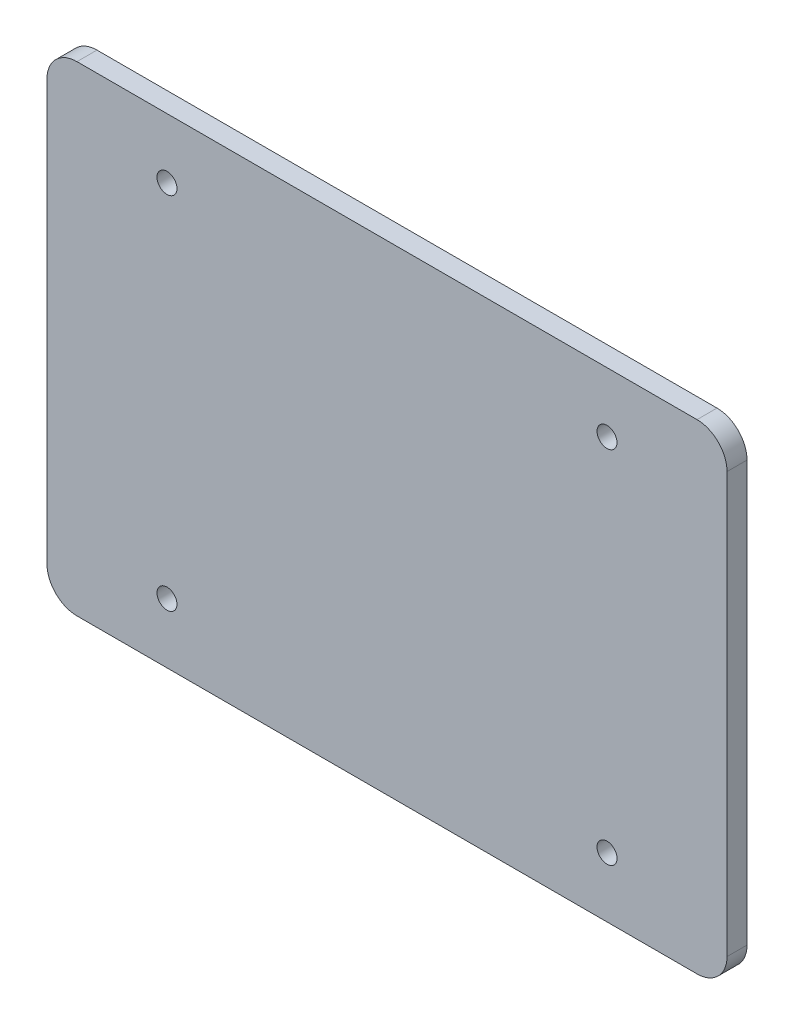
SolidWorks part; units mm, degrees
ref_plane "前视基准面" through (0, 0, 0) normal (0, 0, 1) x (1, 0, 0)
ref_plane "上视基准面" through (0, 0, 0) normal (0, 1, 0) x (1, 0, 0)
ref_plane "右视基准面" through (0, 0, 0) normal (1, 0, 0) x (0, 0, -1)
sketch "草图1" plane through (0, 0, 0) normal (0, 0, 1) x (1, 0, 0)
  line L1 (-170, 120) -> (170, 120)
  line L2 (-170, 120) -> (-170, -120)
  line L3 (-170, -120) -> (170, -120)
  line L4 (170, 120) -> (170, -120)
  line L5 (-170, 120) -> (170, -120) construction
  line L6 (-170, -120) -> (170, 120) construction
  point P0 (0, 0)
  dimension "D1" = 240
  dimension "D2" = 340
extrude "凸台-拉伸1" add sketch "草图1" along normal blind 10
sketch "草图2" plane through (0, 0, 10) normal (0, 0, 1) x (1, 0, 0)
  line L0 (170, 120) -> (-170, 120) construction
  line L1 (170, -120) -> (170, 120) construction
  line L2 (-170, 120) -> (-170, -120) construction
  line L3 (0, 0) -> (170, 0)
  circle A0 centre (110, 90) radius 5
  circle A1 centre (-110, 90) radius 5
  circle A4 centre (110, -90) radius 5
  circle A5 centre (-110, -90) radius 5
  dimension "D3" = 10
  dimension "D4" = 10
  dimension "D1" = 30
  dimension "D2" = 60
  dimension "D5" = 60
fillet "圆角1" radius 15 1 edges at (-170, 120, 5)
fillet "圆角2" radius 15 1 edges at (170, 120, 5)
fillet "圆角3" radius 15 1 edges at (170, -120, 5)
fillet "圆角4" radius 15 1 edges at (-170, -120, 5)
extrude "切除-拉伸1" cut sketch "草图2" against normal blind 10 contours A1 | A0 | A5 | A4
